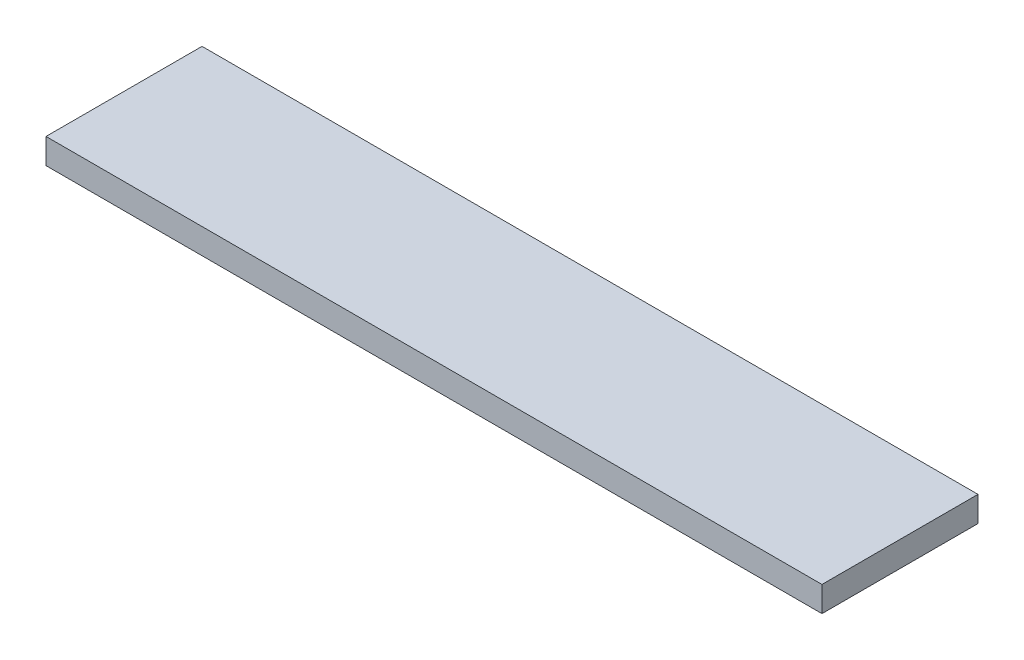
SolidWorks part; units mm, degrees
material "Pine"
ref_plane "Front Plane" through (0, 0, 0) normal (0, 0, 1) x (1, 0, 0)
ref_plane "Top Plane" through (0, 0, 0) normal (0, 1, 0) x (1, 0, 0)
ref_plane "Right Plane" through (0, 0, 0) normal (1, 0, 0) x (0, 0, -1)
sketch "Sketch1" plane through (0, 0, 0) normal (0, 1, 0) x (1, 0, 0)
  line L1 (-423.6906, 404.2151) -> (744.7094, 404.2151)
  line L2 (-423.6906, 404.2151) -> (-423.6906, 169.2651)
  line L3 (-423.6906, 169.2651) -> (744.7094, 169.2651)
  line L4 (744.7094, 404.2151) -> (744.7094, 169.2651)
  dimension "D1" = 1168.4
  dimension "D2" = 234.95
extrude "Boss-Extrude1" add sketch "Sketch1" along normal blind 38.1 contours L1 L4 L3 L2
